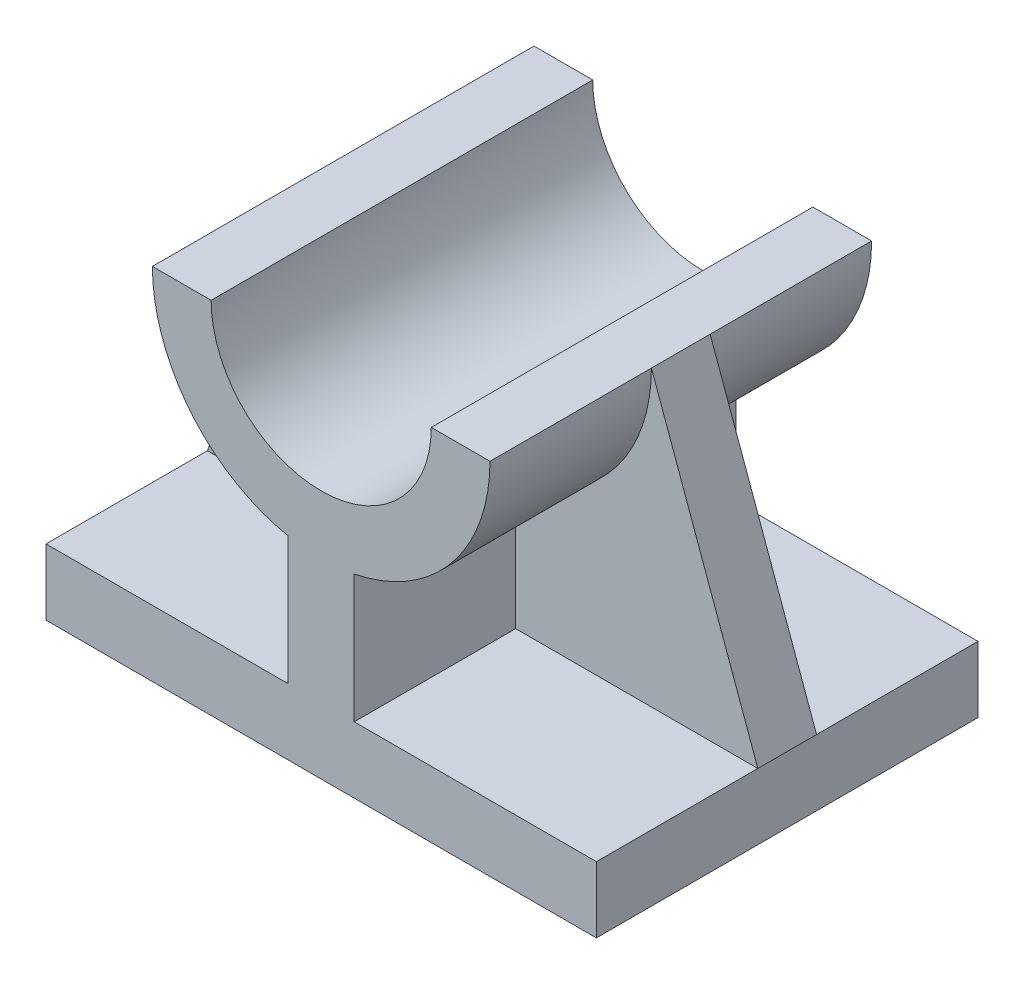
SolidWorks part; units mm, degrees
material "E-Glass Fiber"
ref_plane "Front Plane" through (0, 0, 0) normal (0, 0, 1) x (1, 0, 0)
ref_plane "Top Plane" through (0, 0, 0) normal (0, 1, 0) x (1, 0, 0)
ref_plane "Right Plane" through (0, 0, 0) normal (1, 0, 0) x (0, 0, -1)
sketch "Sketch2" plane through (0, 0, 0) normal (0, 0, 1) x (1, 0, 0)
  line L0 (-27.0783, 0) -> (47.9217, 0)
  line L1 (-27.0783, 0) -> (-27.0783, 9)
  line L2 (-27.0783, 9) -> (5.9217, 9)
  line L3 (14.9217, 9) -> (14.9217, 26.4445)
  line L4 (10.4217, 0) -> (10.4217, 49) construction
  line L5 (47.9217, 0) -> (47.9217, 9)
  line L6 (47.9217, 9) -> (14.9217, 9)
  line L7 (5.9217, 9) -> (5.9217, 26.45)
  line L8 (-12.5783, 49) -> (-4.5783, 49)
  line L9 (25.4217, 49) -> (33.4217, 49)
  line L10 (5.9217, 26.449) -> (5.9217, 26.45)
  arc A0 (14.9217, 26.4445) -> (33.4217, 49) centre (10.4217, 49) ccw
  arc A1 (-4.5783, 49) -> (25.4217, 49) centre (10.4217, 49) ccw
  arc A2 (-12.5783, 49) -> (5.9217, 26.4445) centre (10.4217, 49) ccw
  dimension "D8" = 30
  dimension "D9" = 46
  dimension "D10" = 26.449
  dimension "D1" = 9
  dimension "D2" = 75
  dimension "D3" = 17.45
  dimension "D4" = 33
  dimension "D5" = 9
  dimension "D6" = 27.0783
  dimension "D7" = 49
extrude "Boss-Extrude1" add sketch "Sketch2" along normal blind 52
ref_plane "Plane1" through (45.2395, 16.3993, 0) normal (-0.9401, -0.3408, 0) x (0, 0, 1)
sketch "Sketch4" plane through (45.2395, 16.3993, 0) normal (-0.9401, -0.3408, 0) x (0, 0, 1)
  line L0 (26, 34.6766) -> (26, -7.8705)
  line L1 (52, 34.6766) -> (0, 34.6766) construction
  line L2 (52, -7.8705) -> (0, -7.8705) construction
rib "Rib1" sketch "Sketch4" sketch "Sketch4" thickness 8 extrusion direction normal to sketch draft on no parameters "D1"=8
ref_plane "Plane2" through (-26.8169, 9.7211, 0) normal (-0.9401, 0.3408, 0) x (0, 0, 1)
sketch "Sketch5" plane through (-26.8169, 9.7211, 0) normal (-0.9401, 0.3408, 0) x (0, 0, 1)
  line L0 (26, 41.78) -> (26, -0.767)
  line L1 (52, 41.78) -> (0, 41.78) construction
  line L2 (52, -0.767) -> (0, -0.767) construction
rib "Rib2" sketch "Sketch5" sketch "Sketch5" thickness 8 extrusion direction normal to sketch draft on no parameters "D1"=8
